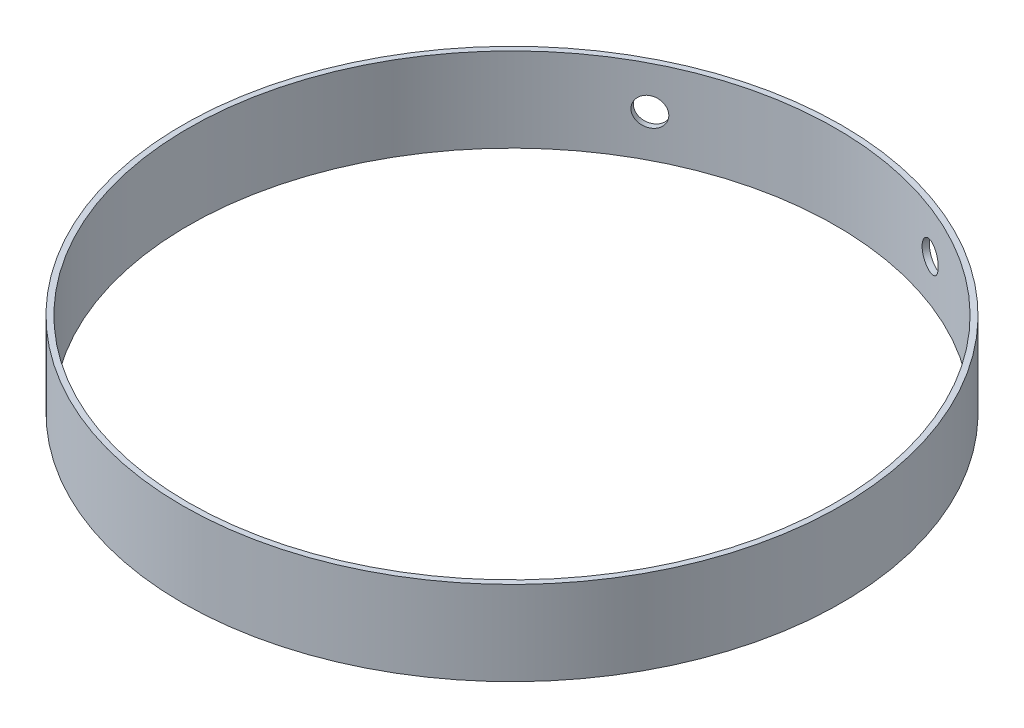
SolidWorks part; units mm, degrees
ref_plane "Front Plane" through (0, 0, 0) normal (0, 0, 1) x (1, 0, 0)
ref_plane "Top Plane" through (0, 0, 0) normal (0, 1, 0) x (1, 0, 0)
ref_plane "Right Plane" through (0, 0, 0) normal (1, 0, 0) x (0, 0, -1)
sketch "Sketch1" plane through (0, 0, 0) normal (0, 1, 0) x (1, 0, 0)
  circle A0 centre (0, 0) radius 74.5363
  circle A1 centre (0, 0) radius 73.2663
  dimension "D1" = 149.0726
  dimension "D2" = 146.5326
extrude "Boss-Extrude1" add sketch "Sketch1" along normal blind 19.05
hole_wizard "1/4 (0.25) Diameter Hole1" positions "3DSketch5" profile "Sketch10" hole size "1/4" standard "ANSI Inch"
sketch3d "3DSketch5"
  line L0 (0, 0, 0) -> (0, 19.05, 0)
  line L1 (0, 19.05, 0) -> (0, 0, 0) construction
  point P0 (-34.3809, 9.525, -66.1333)
  point P2 (26.7362, 9.525, -69.5761)
  dimension "D1" = 9.525
  dimension "D2" = 9.525
  dimension "D3" = 61.214
sketch "Sketch10" plane through (-34.3809, 9.525, -66.1333) normal (0, 1, 0) x (-0.8873, 0, 0.4613)
  line L0 (0, 0) -> (0, 1.27)
  line L1 (0, 1.27) -> (3.175, 1.27)
  line L2 (3.175, 1.27) -> (3.175, 0)
  line L5 (3.175, 0) -> (0, 0)
  line L11 (0, -6.35) -> (0, 107.95) construction
  dimension "Thru Hole Dia." = 6.35
  dimension "Thru Hole Depth" = 1.27
